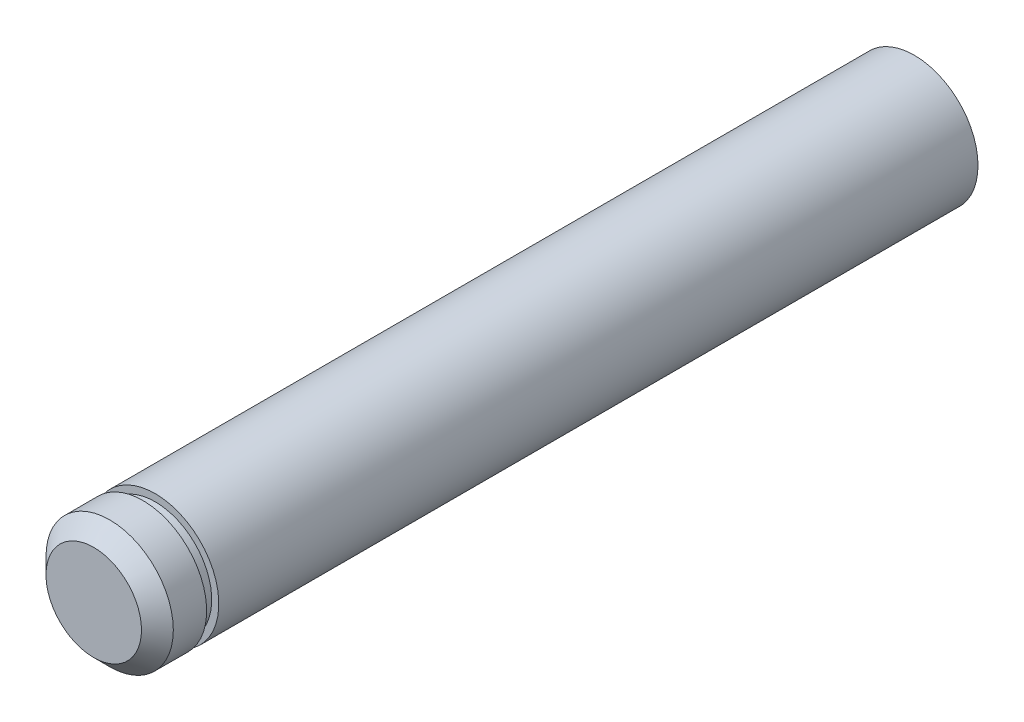
SolidWorks part; units mm, degrees
ref_plane "Front Plane" through (0, 0, 0) normal (0, 0, 1) x (1, 0, 0)
ref_plane "Top Plane" through (0, 0, 0) normal (0, 1, 0) x (1, 0, 0)
ref_plane "Right Plane" through (0, 0, 0) normal (1, 0, 0) x (0, 0, -1)
sketch "Sketch1" plane through (0, 0, 0) normal (0, 0, 1) x (1, 0, 0)
  circle A0 centre (0, 0) radius 4
extrude "Boss-Extrude1" add sketch "Sketch1" along normal blind 51.562
sketch "Sketch2" plane through (0, 0, 0) normal (0, 1, 0) x (1, 0, 0)
  line L0 (0, 0) -> (0, -60.3417) construction
  line L1 (3.556, -47.705) -> (3.556, -48.467)
  line L2 (4, -51.562) -> (4, 0) construction
  line L3 (4, -47.705) -> (4, -48.467)
  line L4 (3.556, -48.467) -> (4, -48.467)
  line L5 (3.556, -47.705) -> (4, -47.705)
revolve "Cut-Revolve1" cut sketch "Sketch2" angle 360 about L0
chamfer "Chamfer2" distance 1 angle 45 1 edges at (4, 0, 51.562)
hole_wizard "#10-32 Tapped Hole2" positions "Sketch7" profile "Sketch6" tap size "#10-32" standard "Ansi Inch"
sketch "Sketch7" plane through (0, 0, 0) normal (0, 0, -1) x (-1, 0, 0)
  point P0 (0, 0)
sketch "Sketch6" plane through (0, 0, 0) normal (1, 0, 0) x (0, 1, 0)
  line L0 (0, 0) -> (0, 13.9133)
  line L1 (0, 13.9133) -> (2.0193, 12.7)
  line L2 (2.0193, 12.7) -> (2.0193, 0)
  line L5 (2.0193, 0) -> (0, 0)
  line L10 (0, 13.9133) -> (-2.0193, 12.7) construction
  line L11 (0, -6.35) -> (0, 107.95) construction
  dimension "Tap Drill Dia." = 4.0386
  dimension "Tap Drill Depth" = 12.7
  dimension "Drill Angle" = 118
cosmetic thread "Hole Thread1" parameters "D1"=9.652, "D2"=4.826
